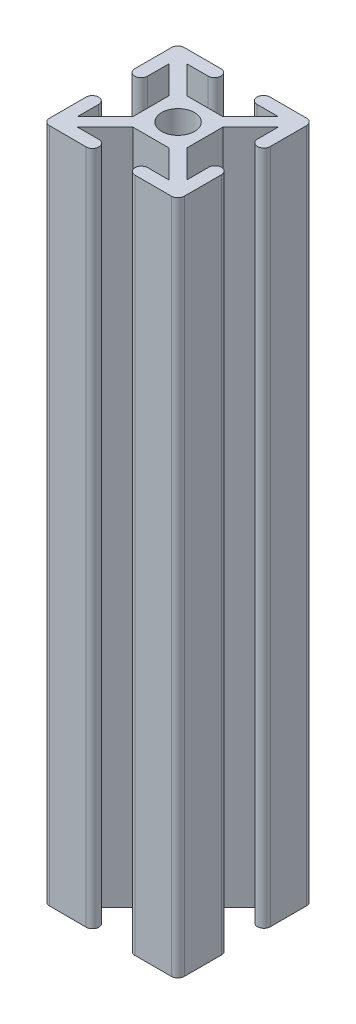
SolidWorks part; units mm, degrees
ref_plane "Alzado" through (0, 0, 0) normal (0, 0, 1) x (1, 0, 0)
ref_plane "Planta" through (0, 0, 0) normal (0, 1, 0) x (1, 0, 0)
ref_plane "Vista lateral" through (0, 0, 0) normal (1, 0, 0) x (0, 0, -1)
sketch "Croquis2" plane through (0, 0, 0) normal (0, 1, 0) x (1, 0, 0)
  line L0 (6.6213, 7.9369) -> (6.6213, 9.3619) construction
  line L1 (25.6741, -8.2131) -> (30.3991, -8.2131)
  line L2 (5.1963, 17.5118) -> (5.1963, 9.3619)
  line L3 (6.6213, 18.9368) -> (14.7713, 18.9368)
  line L4 (25.6213, 18.9368) -> (33.7713, 18.9368)
  line L5 (10.0991, -8.2131) -> (14.8241, -8.2131)
  line L6 (14.1963, 7.9369) -> (14.1963, -0.0631)
  line L7 (5.2491, -1.4881) -> (5.2491, -9.6381)
  line L8 (6.6477, -11.0367) -> (14.8241, -11.0631)
  line L9 (35.1963, 17.5118) -> (35.1963, 9.4656)
  line L10 (8.0463, 14.0869) -> (8.0463, 9.3619)
  line L11 (35.1963, -1.3844) -> (35.1963, -9.6381)
  line L12 (16.1963, 17.5118) -> (14.7713, 17.5118) construction
  line L13 (25.6741, -11.0631) -> (33.7713, -11.0631)
  line L14 (10.0463, 16.0868) -> (14.7713, 16.0868)
  line L15 (8.0463, -1.4881) -> (8.0463, -6.2131)
  line L16 (24.1963, 17.5118) -> (25.6213, 17.5118) construction
  line L17 (25.6213, 16.0868) -> (30.3463, 16.0868)
  line L18 (33.7713, 8.0406) -> (33.7713, 9.4656) construction
  line L19 (16.1963, 9.9368) -> (10.0463, 16.0868)
  line L20 (32.3463, 14.0868) -> (32.3463, 9.4656)
  line L21 (33.7713, 0.0406) -> (33.7713, -1.3844) construction
  line L22 (14.1963, 7.9369) -> (8.0463, 14.0869)
  line L23 (32.3463, -1.3844) -> (32.3463, -6.2132)
  line L24 (24.2491, -9.6381) -> (25.6741, -9.6381) construction
  line L25 (14.1963, -0.0631) -> (8.0463, -6.2131)
  line L26 (16.1963, 9.9368) -> (24.1963, 9.9368)
  line L27 (24.1963, 9.9368) -> (30.3463, 16.0868)
  line L28 (6.6477, -0.0631) -> (6.6477, -1.4881) construction
  line L29 (10.0991, -8.2131) -> (16.2491, -2.0631)
  line L30 (16.2491, -2.0631) -> (24.2491, -2.0631)
  line L31 (24.2491, -2.0631) -> (30.3991, -8.2131)
  line L32 (16.2491, -9.6381) -> (14.8241, -9.6381) construction
  line L33 (26.1963, -0.0632) -> (32.3463, -6.2132)
  line L34 (26.1963, 7.9368) -> (32.3463, 14.0868)
  line L35 (26.1963, 7.9368) -> (26.1963, -0.0632)
  circle A0 centre (20.2491, 3.9369) radius 3.645
  arc A1 (5.1963, 9.3619) -> (8.0463, 9.3619) centre (6.6213, 9.3619) ccw
  arc A2 (14.7713, 16.0868) -> (14.7713, 18.9368) centre (14.7713, 17.5118) ccw
  arc A3 (25.6213, 18.9368) -> (25.6213, 16.0868) centre (25.6213, 17.5118) ccw
  arc A4 (32.3463, 9.4656) -> (35.1963, 9.4656) centre (33.7713, 9.4656) ccw
  arc A5 (35.1963, -1.3844) -> (32.3463, -1.3844) centre (33.7713, -1.3844) ccw
  arc A6 (25.6741, -8.2131) -> (25.6741, -11.0631) centre (25.6741, -9.6381) ccw
  arc A7 (8.0463, -1.4881) -> (5.2491, -1.4881) centre (6.6477, -1.4881) ccw
  arc A8 (14.8241, -11.0631) -> (14.8241, -8.2131) centre (14.8241, -9.6381) ccw
  arc A9 (5.2491, -9.6381) -> (6.6477, -11.0367) centre (6.6477, -9.6381) ccw
  arc A10 (33.7713, -11.0631) -> (35.1963, -9.6381) centre (33.7713, -9.6381) ccw
  arc A11 (35.1963, 17.5118) -> (33.7713, 18.9368) centre (33.7713, 17.5118) ccw
  arc A12 (6.6213, 18.9368) -> (5.1963, 17.5118) centre (6.6213, 17.5118) ccw
  dimension "D1" = 7.29
  dimension "D2" = 1.425
  dimension "D3" = 1.425
  dimension "D4" = 1.425
  dimension "D5" = 1.425
  dimension "D6" = 1.425
  dimension "D7" = 1.425
  dimension "D8" = 1.425
  dimension "D9" = 1.425
extrude "Saliente-Extruir1" add sketch "Croquis2" along normal blind 150
